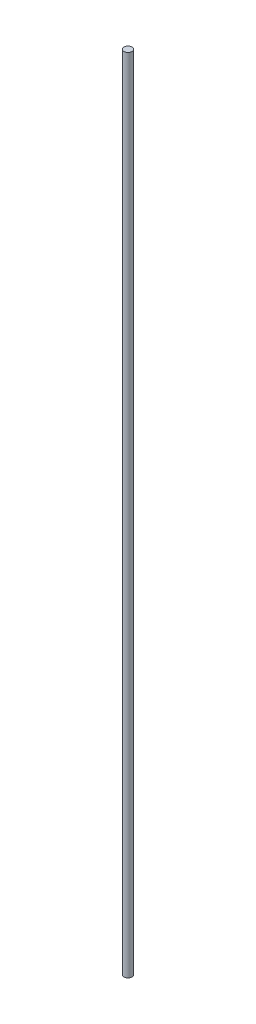
SolidWorks part; units mm, degrees
material "AISI 1020"
ref_plane "Front Plane" through (0, 0, 0) normal (0, 0, 1) x (1, 0, 0)
ref_plane "Top Plane" through (0, 0, 0) normal (0, 1, 0) x (1, 0, 0)
ref_plane "Right Plane" through (0, 0, 0) normal (1, 0, 0) x (0, 0, -1)
sketch "Sketch1" plane through (0, 0, 0) normal (0, 1, 0) x (1, 0, 0)
  circle A0 centre (0, 0) radius 4
  dimension "D1" = 8
extrude "Boss-Extrude1" add sketch "Sketch1" along normal blind 410 and the other way blind 400
